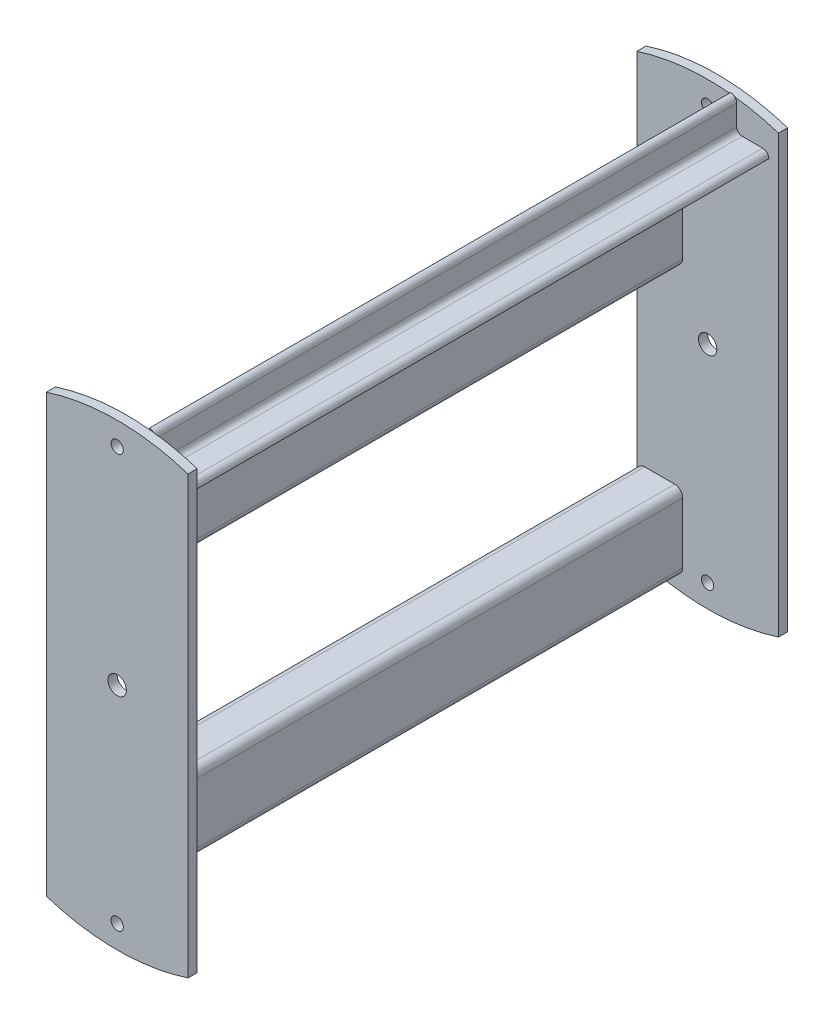
SolidWorks part; units mm, degrees
ref_plane "Płaszczyzna przednia" through (0, 0, 0) normal (0, 0, 1) x (1, 0, 0)
ref_plane "Płaszczyzna górna" through (0, 0, 0) normal (0, 1, 0) x (1, 0, 0)
ref_plane "Płaszczyzna prawa" through (0, 0, 0) normal (1, 0, 0) x (0, 0, -1)
sketch "Szkic1" plane through (0, 0, 0) normal (0, 0, 1) x (1, 0, 0)
  line L0 (0, 124.1025) -> (0, -135) construction
  circle A0 centre (0, 0) radius 150
  point P5 (0, 135)
  point P7 (0, 0)
  dimension "D1" = 300
  dimension "D2" = 270
  dimension "roz" = 135
extrude "Dodanie-wyciągnięcie1" add sketch "Szkic1" along normal blind 6 contours A0
hole_wizard "Otwory ustalające Ø12.0mm1" positions "Szkic2" profile "Szkic3" hole size "Ø12.0" standard "Ansi Metric" end condition through all
sketch "Szkic2" plane through (0, 0, 0) normal (0, 0, -1) x (-1, 0, 0)
  point P0 (0, 0)
sketch "Szkic3" plane through (0, 0, 0) normal (1, 0, 0) x (0, 1, 0)
  line L0 (0, 0) -> (0, 6)
  line L1 (0, 6) -> (6, 6)
  line L2 (6, 6) -> (6, 0)
  line L5 (6, 0) -> (0, 0)
  line L11 (0, -6.35) -> (0, 107.95) construction
  dimension "Średnica otworu na wylot" = 12
  dimension "Głębokość otworu na wylot" = 6
hole_wizard "Otwory ustalające Ø8.0mm1" positions "Szkic4" profile "Szkic5" hole size "Ø8.0" standard "Ansi Metric" end condition through all
sketch "Szkic4" plane through (0, 0, 0) normal (0, 0, -1) x (-1, 0, 0)
  point P0 (0, 135)
  point P3 (0, -135)
sketch "Szkic5" plane through (0, 135, 0) normal (1, 0, 0) x (0, 1, 0)
  line L0 (0, 0) -> (0, 6)
  line L1 (0, 6) -> (4, 6)
  line L2 (4, 6) -> (4, 0)
  line L5 (4, 0) -> (0, 0)
  line L11 (0, -6.35) -> (0, 107.95) construction
  dimension "Średnica otworu na wylot" = 8
  dimension "Głębokość otworu na wylot" = 6
sketch "Szkic6" plane through (0, 0, 0) normal (0, 0, -1) x (-1, 0, 0)
  line L0 (-46.3023, -166.476) -> (-243.401, -95.5234)
  line L1 (-46.3023, 166.476) -> (46.3023, 166.476)
  line L2 (-46.3023, 166.476) -> (-46.3023, -166.476)
  line L3 (-46.3023, -166.476) -> (46.3023, -166.476)
  line L4 (46.3023, 166.476) -> (46.3023, -166.476)
  line L5 (-46.3023, 166.476) -> (46.3023, -166.476) construction
  line L6 (-46.3023, -166.476) -> (46.3023, 166.476) construction
  line L7 (-243.401, -95.5234) -> (-223.7189, 137.7741)
  line L8 (-223.7189, 137.7741) -> (-46.3023, 166.476)
  line L9 (46.3023, 166.476) -> (218.7328, 144.5972)
  line L10 (218.7328, 144.5972) -> (226.8681, -150.633)
  line L11 (226.8681, -150.633) -> (46.3023, -166.476)
  point P0 (0, 0)
  circle M4 centre (0, 0) radius 150
extrude "Wytnij-wyciągnięcie1" cut sketch "Szkic6" against normal blind 6 contours L8 L7 L0 L2 M4 | L11 L10 L9 L4 M4 | L4 M4 | L2 M4
sketch "Szkic14" plane through (0, 0, 0) normal (0, 0, -1) x (-1, 0, 0)
  line L0 (31.3023, 128.3268) -> (31.3023, -121.2412) construction
  line L1 (46.3023, -142.6748) -> (46.3023, 142.6748) construction
  circle A1 centre (0, 135) radius 4 construction
  point P4 (31.3023, 60)
  point P5 (31.3023, -115)
  point P6 (-15, 125)
  dimension "D4" = 10
  dimension "D5" = 15
  dimension "D1" = 15
  dimension "D2" = 175
  dimension "D3" = 60
sketch3d "Szkic 3D6"
  line L0 (-31.3023, 60, 0) -> (-31.3023, 60, -380)
  line L1 (-31.3023, -115, 0) -> (-31.3023, -115, -380)
  line L2 (15, 125, 0) -> (15, 125, -380)
  point P10 (0, 0, 0)
  point P12 (0, 0, 0)
  dimension "D1" = 380
  dimension "prof" = 380
  dimension "D2" = 380
ref_plane "Płaszczyzna3" through (15, 125, 0) normal (0, 0, -1) x (1, 0, 0)
other "Rura prostokątna 50 X 30 X 2.6(1)"
ref_plane "Płaszczyzna4" through (-31.3023, 60, 0) normal (0, 0, -1) x (1, 0, 0)
sketch "Sketch14" plane through (-31.3023, 60, 0) normal (0, 0, -1) x (1, 0, 0)
  line L0 (-9.8, -22.4) -> (9.8, -22.4)
  line L1 (-12.4, -19.8) -> (-12.4, 19.8)
  line L2 (9.8, 22.4) -> (-9.8, 22.4)
  line L3 (12.4, 19.8) -> (12.4, -19.8)
  line L4 (-9.8, -25) -> (9.8, -25)
  line L5 (-15, -19.8) -> (-15, 19.8)
  line L6 (9.8, 25) -> (-9.8, 25)
  line L7 (15, 19.8) -> (15, -19.8)
  arc A0 (15, 19.8) -> (9.8, 25) centre (9.8, 19.8) ccw
  arc A1 (9.8, -25) -> (15, -19.8) centre (9.8, -19.8) ccw
  arc A2 (-15, -19.8) -> (-9.8, -25) centre (-9.8, -19.8) ccw
  arc A3 (-9.8, 25) -> (-15, 19.8) centre (-9.8, 19.8) ccw
  arc A4 (-9.8, 22.4) -> (-12.4, 19.8) centre (-9.8, 19.8) ccw
  arc A5 (12.4, 19.8) -> (9.8, 22.4) centre (9.8, 19.8) ccw
  arc A6 (9.8, -22.4) -> (12.4, -19.8) centre (9.8, -19.8) ccw
  arc A7 (-12.4, -19.8) -> (-9.8, -22.4) centre (-9.8, -19.8) ccw
  point P0 (0, 25)
  point P1 (15, 0)
  point P2 (0, -25)
  point P3 (-15, 0)
  point P4 (-15, 25)
  point P5 (15, 25)
  point P6 (15, -25)
  point P7 (-15, -25)
  point P8 (0, 0)
  point P33 (0, 0)
  point P35 (0, 0)
  dimension "D1" = 5.2
  dimension "Thickness" = 2.6
  dimension "V_leg" = 50
  dimension "H_leg" = 30
pattern_linear "Szyk liniowy1" count 2 spacing 386 along (0, 0, -1) of bodies 104
other "Kątownik stalowy 25 X 25 X 4(1)"
ref_plane "Płaszczyzna5" through (15, 125, 0) normal (0, 0, -1) x (0, 1, 0)
sketch "Sketch115" plane through (15, 125, 0) normal (0, 0, -1) x (0, 1, 0)
  line L0 (0, 0) -> (0, 25)
  line L1 (0, 12.5) -> (4, 12.5) construction
  line L2 (4, 21) -> (4, 7.5)
  line L3 (7.5, 4) -> (21, 4)
  line L4 (12.5, 4) -> (12.5, 0) construction
  line L5 (25, 0) -> (0, 0)
  arc A0 (25, 0) -> (21, 4) centre (21, 0) ccw
  arc A1 (0, 25) -> (4, 21) centre (0, 21) cw
  arc A2 (7.5, 4) -> (4, 7.5) centre (7.5, 7.5) cw
  point P10 (12.5, 0)
  point P14 (0, 12.5)
  point P15 (4, 12.5)
  point P16 (12.5, 4)
  point P17 (4, 25)
  point P18 (25, 4)
  point P21 (0, 0)
  dimension "D2" = 4
  dimension "D3" = 25
  dimension "Radius_1" = 3.5
  dimension "D1" = 4
equation "\"profil\"=311.667"
equation "\"D1@Szkic 3D6\"=\"prof\""
equation "\"D2@Szkic 3D6\"=\"prof\""
